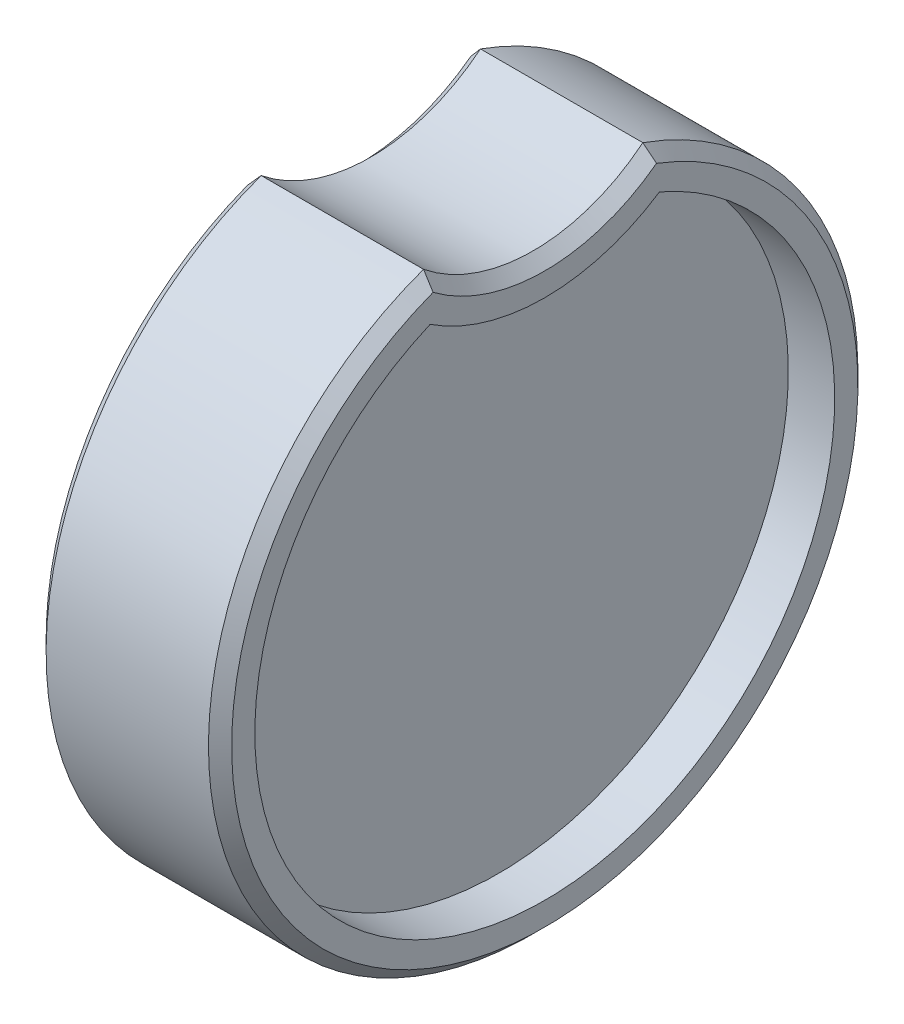
SolidWorks part; units mm, degrees
ref_plane "Front Plane" through (0, 0, 0) normal (0, 0, 1) x (1, 0, 0)
ref_plane "Top Plane" through (0, 0, 0) normal (0, 1, 0) x (1, 0, 0)
ref_plane "Right Plane" through (0, 0, 0) normal (1, 0, 0) x (0, 0, -1)
sketch "Sketch1" plane through (0, 0, 0) normal (1, 0, 0) x (0, 0, -1)
  circle A0 centre (0, 0) radius 28
  dimension "D1" = 56
extrude "Boss-Extrude1" add sketch "Sketch1" along normal mid plane 16
sketch "Sketch2" plane through (8, 0, 0) normal (1, 0, 0) x (0, 0, -1)
  circle A0 centre (0, 38) radius 15
  dimension "D1" = 30
  dimension "D2" = 38
extrude "Cut-Extrude1" cut sketch "Sketch2" against normal through all
chamfer "Chamfer1" distance 1 angle 45 6 edges at (-8, 23, 0) (-8, -28, 0) (8, 23, 0) (8, -28, 0) (0, 26.3553, -9.4552) (0, 26.3553, 9.4552)
sketch "Sketch3" plane through (8, 0, 0) normal (1, 0, 0) x (0, 0, -1)
  arc A1 (-9.8901, 22.9605) -> (9.8901, 22.9605) centre (0, 0) ccw
  arc A10 (-9.8901, 22.9605) -> (9.8901, 22.9605) centre (0, 0) ccw
  arc A12 (-9.8901, 22.9605) -> (9.8901, 22.9605) centre (0, 38) ccw
  arc A13 (-9.8901, 22.9605) -> (9.8901, 22.9605) centre (0, 38) ccw
  dimension "D1" = 2
extrude "Cut-Extrude2" cut sketch "Sketch3" against normal blind 4
mirror "Mirror1" about plane through (0, 0, 0) normal (1, 0, 0) of "Cut-Extrude2"
sketch "Sketch4" plane through (8, 0, 0) normal (1, 0, 0) x (0, 0, -1)
  line L0 (0, -34.4641) -> (-8.6603, -39.4641)
  line L1 (-8.6603, -39.4641) -> (8.6603, -39.4641)
  line L2 (8.6603, -39.4641) -> (0, -34.4641)
  circle A0 centre (0, 0) radius 27 construction
  dimension "D1" = 120
  dimension "D2" = 5
extrude "Cut-Extrude3" [suppressed] cut sketch "Sketch4" against normal through all
pattern_circular "CirPattern1" [suppressed] count 55 over 360
